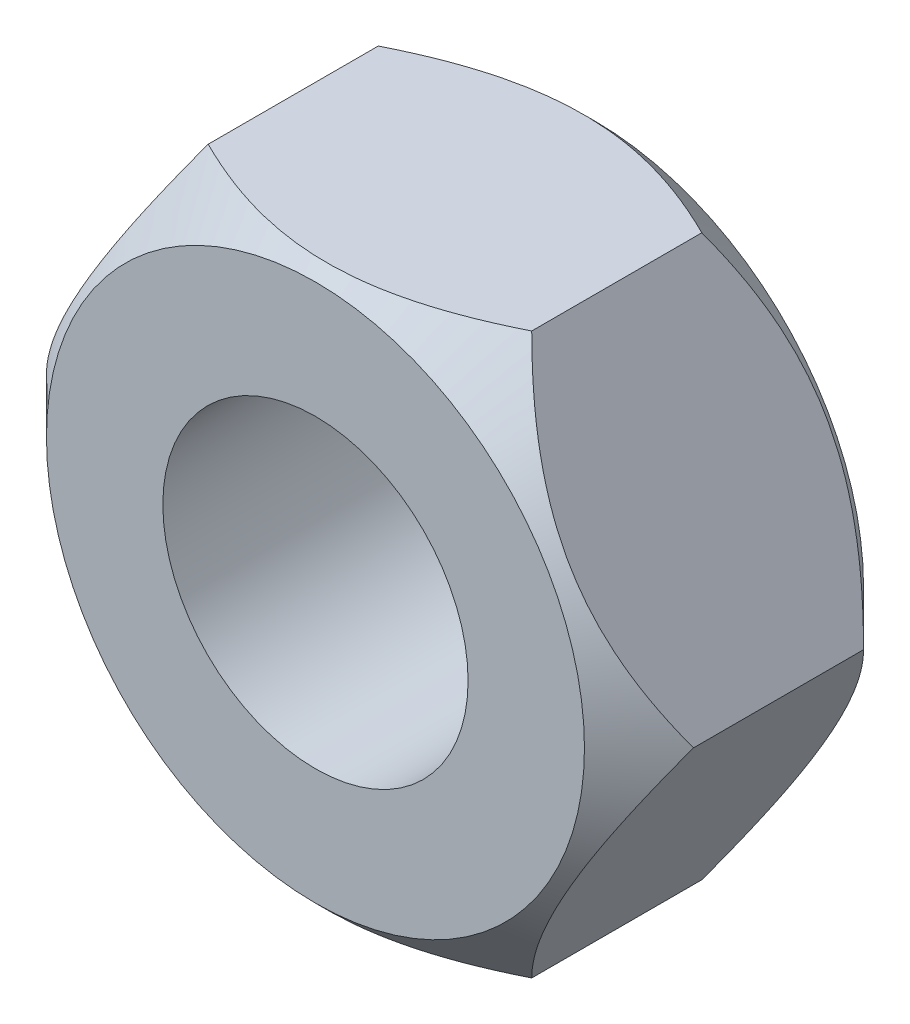
SolidWorks part; units mm, degrees
ref_plane "Front Plane" through (0, 0, 0) normal (0, 0, 1) x (1, 0, 0)
ref_plane "Top Plane" through (0, 0, 0) normal (0, 1, 0) x (1, 0, 0)
ref_plane "Right Plane" through (0, 0, 0) normal (1, 0, 0) x (0, 0, -1)
sketch "Sketch1" plane through (0, 0, 0) normal (0, 0, 1) x (1, 0, 0)
  line L1 (7.419, 0) -> (3.7095, 6.425)
  line L2 (3.7095, 6.425) -> (-3.7095, 6.425)
  line L3 (-3.7095, 6.425) -> (-7.419, 0)
  line L4 (-7.419, 0) -> (-3.7095, -6.425)
  line L5 (-3.7095, -6.425) -> (3.7095, -6.425)
  line L6 (3.7095, -6.425) -> (7.419, 0)
  circle A0 centre (0, 0) radius 6.425 construction
  dimension "D1" = 12.85
extrude "Boss-Extrude1" add sketch "Sketch1" along normal blind 6.4
hole_wizard "Tap Drill for M8x1.0 Tap1" positions "Sketch3" profile "Sketch2" hole size "M8x1.0" standard "ANSI Metric"
sketch "Sketch3" plane through (0, 0, 0) normal (0, 0, -1) x (-1, 0, 0)
  point P0 (0, 0)
sketch "Sketch2" plane through (0, 0, 0) normal (1, 0, 0) x (0, 1, 0)
  line L0 (0, 0) -> (0, 16)
  line L1 (0, 16) -> (3.5, 16)
  line L2 (3.5, 16) -> (3.5, 0)
  line L5 (3.5, 0) -> (0, 0)
  line L10 (0, 16) -> (-3.5, 16) construction
  line L11 (0, -6.35) -> (0, 107.95) construction
  dimension "Hole Dia." = 7
  dimension "Hole Depth" = 16
  dimension "Drill Angle" = 180
ref_plane "Plane1" through (0, 0, 0) normal (0, -1, 0) x (-1, 0, 0)
sketch "Sketch4" plane through (0, 0, 0) normal (0, -1, 0) x (-1, 0, 0)
  line L0 (-7.419, 0) -> (-7.419, -1.25)
  line L1 (-7.419, -6.4) -> (-7.419, 0) construction
  line L2 (-7.419, -1.25) -> (-6.169, 0)
  line L4 (-6.169, 0) -> (-7.419, 0)
  line L5 (-7.419, -3.2) -> (7.419, -3.2) construction
  line L6 (7.419, -6.4) -> (7.419, 0) construction
  line L7 (-7.419, -6.4) -> (-7.419, -5.15)
  line L8 (-7.419, -5.15) -> (-6.169, -6.4)
  line L9 (-6.169, -6.4) -> (-7.419, -6.4)
  dimension "D1" = 1.25
  dimension "D2" = 45
ref_axis "Axis1" through (0, 0, 6.4) along (0, 0, -1)
revolve "Cut-Revolve1" cut sketch "Sketch4" angle 360 about axis through (0, 0, 6.4) along (0, 0, -1)
